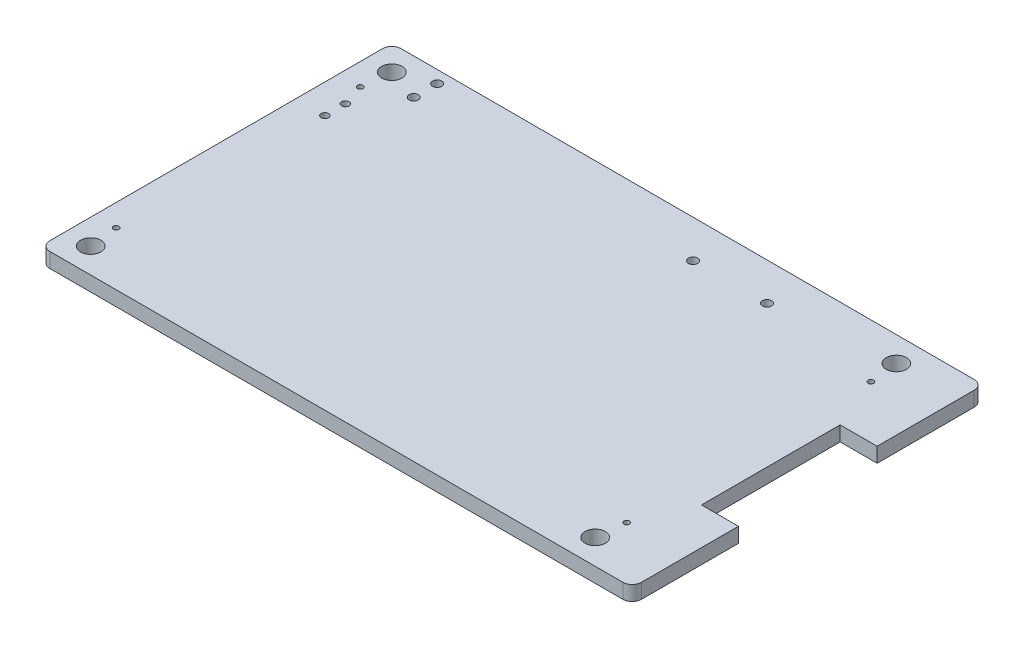
SolidWorks part; units mm, degrees
ref_plane "Front Plane" through (0, 0, 0) normal (0, 0, 1) x (1, 0, 0)
ref_plane "Top Plane" through (0, 0, 0) normal (0, 1, 0) x (1, 0, 0)
ref_plane "Right Plane" through (0, 0, 0) normal (1, 0, 0) x (0, 0, -1)
sketch "Sketch1" plane through (0, 0, 0) normal (0, 1, 0) x (1, 0, 0)
  line L0 (34, -18) -> (34, -7.5)
  line L1 (34, -7.5) -> (30, -7.5)
  line L2 (30, -7.5) -> (30, 7.5)
  line L3 (30, 7.5) -> (34, 7.5)
  line L4 (34, 7.5) -> (34, 18)
  line L5 (33, 19) -> (-29, 19)
  line L6 (-30, 18) -> (-30, -18)
  line L7 (-29, -19) -> (33, -19)
  line L8 (27.29, 16.29) -> (-27.29, -16.29) construction
  line L9 (-15.146, 0) -> (15.315, 0) construction
  line L10 (0, 8.4471) -> (0, -8.4471) construction
  arc A1 (-30, -18) -> (-29, -19) centre (-29, -18) ccw
  circle A4 centre (27.62, 13.2) radius 0.3
  circle A5 centre (27.29, -16.29) radius 1.1
  circle A6 centre (27.62, -13.2) radius 0.3
  circle A7 centre (14.6563, 14.9244) radius 0.5
  circle A8 centre (27.29, 16.29) radius 1.1
  circle A9 centre (6.6676, 14.9208) radius 0.5
  circle A10 centre (-23.7558, 15.1257) radius 0.5
  circle A11 centre (-26.8436, 8.5997) radius 0.4
  circle A12 centre (-27.29, -16.29) radius 1.1
  circle A13 centre (-27.62, -13.2) radius 0.3
  circle A14 centre (-26.8436, 10.8197) radius 0.4
  circle A15 centre (-23.7558, 17.6657) radius 0.5
  circle A16 centre (-27.62, 13.2) radius 0.3
  circle A17 centre (-27.29, 16.29) radius 1.1
  arc A18 (33, -19) -> (34, -18) centre (33, -18) ccw
  arc A19 (34, 18) -> (33, 19) centre (33, 18) ccw
  arc A20 (-29, 19) -> (-30, 18) centre (-29, 18) ccw
  dimension "D5" = 2.2
  dimension "D7" = 15
  dimension "D9" = 1
  dimension "D1" = 64
  dimension "D2" = 38
  dimension "D3" = 54.58
  dimension "D4" = 32.58
  dimension "D6" = 30
  dimension "D8" = 30
extrude "Boss-Extrude1" add sketch "Sketch1" against normal blind 1.6
